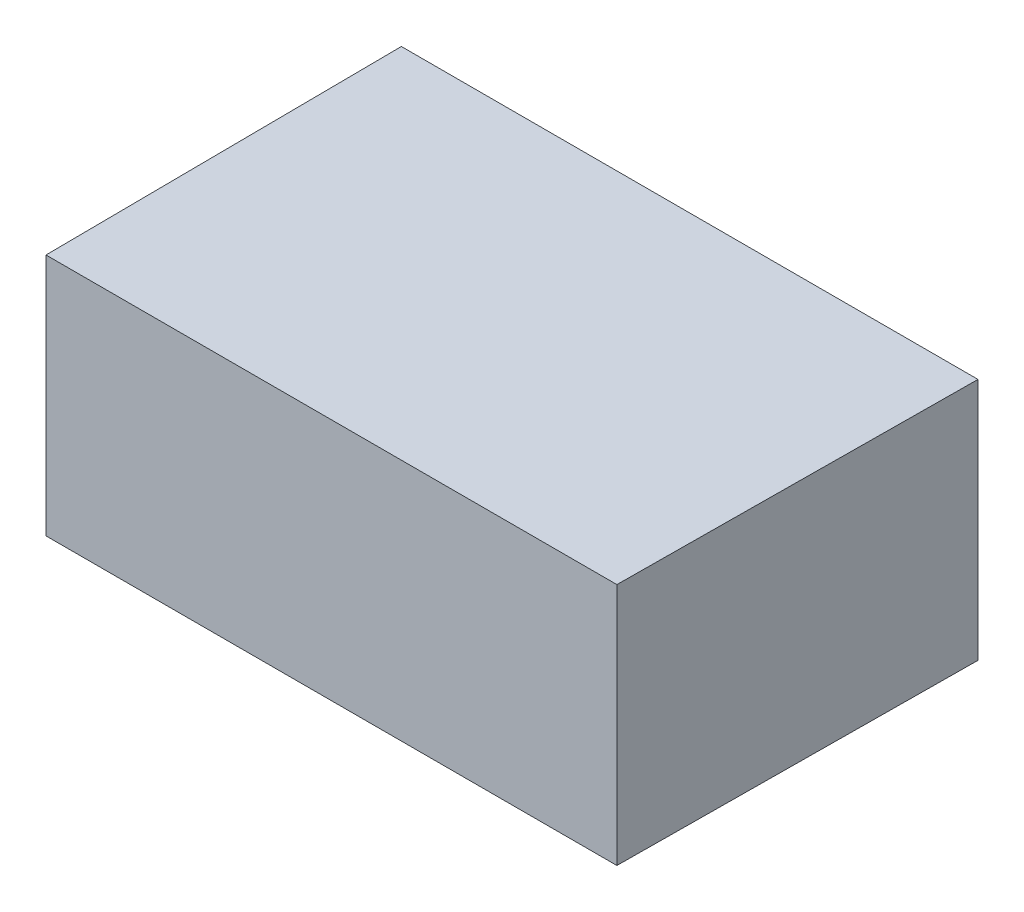
SolidWorks part; units mm, degrees
ref_plane "前视基准面" through (0, 0, 0) normal (0, 0, 1) x (1, 0, 0)
ref_plane "上视基准面" through (0, 0, 0) normal (0, 1, 0) x (1, 0, 0)
ref_plane "右视基准面" through (0, 0, 0) normal (1, 0, 0) x (0, 0, -1)
sketch "草图1" plane through (0, 0, 0) normal (0, 0, 1) x (1, 0, 0)
  line L0 (-101.2013, 0) -> (115.6222, 0) construction
  line L1 (-75.25, 31.75) -> (75.25, 31.75)
  line L2 (-75.25, 31.75) -> (-75.25, -31.75)
  line L3 (-75.25, -31.75) -> (75.25, -31.75)
  line L4 (75.25, 31.75) -> (75.25, -31.75)
  line L5 (0, 88.9082) -> (0, -50.2815) construction
  dimension "D1" = 150.5
  dimension "D2" = 63.5
extrude "拉伸1" add sketch "草图1" along normal blind 93.5
sketch "草图2" plane through (0, 0, 0) normal (0, 0, -1) x (-1, 0, 0)
  line L0 (-75.25, 31.75) -> (75.25, 31.75) construction
  line L1 (59.25, 24.75) -> (60.25, 24.75)
  line L2 (59.25, 24.75) -> (59.25, 17.75)
  line L3 (59.25, 17.75) -> (60.25, 17.75)
  line L4 (60.25, 24.75) -> (60.25, 17.75)
  line L5 (75.25, 31.75) -> (75.25, -31.75) construction
  dimension "D1" = 7
  dimension "D2" = 15
  dimension "D3" = 7
  dimension "D4" = 1
ref_plane "基准面1" through (0, 19, 0) normal (0, 1, 0) x (-1, 0, 0)
sketch "草图3" plane through (0, 19, 0) normal (0, 1, 0) x (-1, 0, 0)
  line L0 (59.75, 0) -> (59.75, -4)
  line L1 (59.25, 0) -> (60.25, 0) construction
  line L2 (59.75, -4) -> (48.75, -4)
  dimension "D1" = 11
  dimension "D2" = 4
sweep "扫描1" add profiles "草图2" path "草图3"
ref_plane "基准面2" through (0, 0, 0) normal (0, 1, 0) x (-1, 0, 0)
mirror "镜向1" about plane through (0, 0, 0) normal (0, 1, 0) of "扫描1"
sketch "草图5" plane through (0, -31.75, 0) normal (0, -1, 0) x (1, 0, 0)
  line L0 (0, -20.8884) -> (0, 117.2599) construction
  line L1 (-75.25, 0) -> (-74.5, 93.5)
  line L2 (-75.25, 93.5) -> (75.25, 93.5) construction
  line L3 (-75.25, 93.5) -> (-75.25, 0)
  line L4 (-74.5, 93.5) -> (-75.25, 93.5)
  line L5 (74.5, 93.5) -> (75.25, 93.5)
  line L6 (75.25, 93.5) -> (75.25, 0)
  line L7 (75.25, 0) -> (74.5, 93.5)
  dimension "D1" = 149
extrude "两侧拔模" cut sketch "草图5" against normal through all
